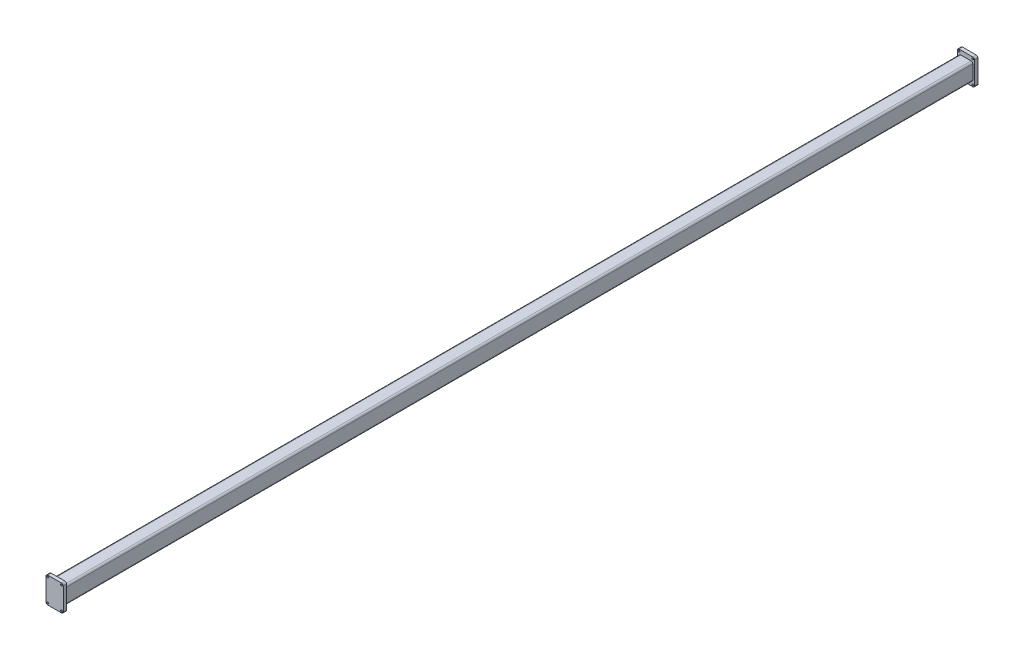
SolidWorks part; units mm, degrees
ref_plane "前视基准面" through (0, 0, 0) normal (0, 0, 1) x (1, 0, 0)
ref_plane "上视基准面" through (0, 0, 0) normal (0, 1, 0) x (1, 0, 0)
ref_plane "右视基准面" through (0, 0, 0) normal (1, 0, 0) x (0, 0, -1)
sketch "草图1" plane through (0, 0, 0) normal (0, 0, 1) x (1, 0, 0)
  line L1 (-4, 7.5) -> (4, 7.5)
  line L2 (-5, 6.5) -> (-5, -6.5)
  line L3 (-4, -7.5) -> (4, -7.5)
  line L4 (5, 6.5) -> (5, -6.5)
  arc A0 (4, -7.5) -> (5, -6.5) centre (4, -6.5) ccw
  arc A1 (-5, -6.5) -> (-4, -7.5) centre (-4, -6.5) ccw
  arc A2 (-4, 7.5) -> (-5, 6.5) centre (-4, 6.5) ccw
  arc A3 (5, 6.5) -> (4, 7.5) centre (4, 6.5) ccw
  circle A4 centre (4, 6.5) radius 0.5
  circle A5 centre (-4, 6.5) radius 0.5
  circle A6 centre (4, -6.5) radius 0.5
  circle A7 centre (-4, -6.5) radius 0.5
  dimension "D1" = 1
extrude "凸台-拉伸1" add sketch "草图1" along normal blind 2
sketch "草图2" plane through (0, 0, 0) normal (0, 0, -1) x (-1, 0, 0)
  line L1 (-3, 5) -> (3, 5)
  line L2 (-4, 4) -> (-4, -4)
  line L3 (-3, -5) -> (3, -5)
  line L4 (4, 4) -> (4, -4)
  arc A0 (-4, -4) -> (-3, -5) centre (-3, -4) ccw
  arc A1 (3, -5) -> (4, -4) centre (3, -4) ccw
  arc A2 (4, 4) -> (3, 5) centre (3, 4) ccw
  arc A3 (-4, 4) -> (-3, 5) centre (-3, 4) cw
  dimension "D1" = 1
extrude "拉伸-薄壁1" add sketch "草图2" along normal blind 263 thin
mirror "镜向1" about plane through (3, -4, -263) normal (0, 0, -1) of bodies 113
scale "缩放比例1" scale about origin uniform scaling yes scale factor 2
scale "缩放比例2" scale about origin uniform scaling yes scale factor 1.7
